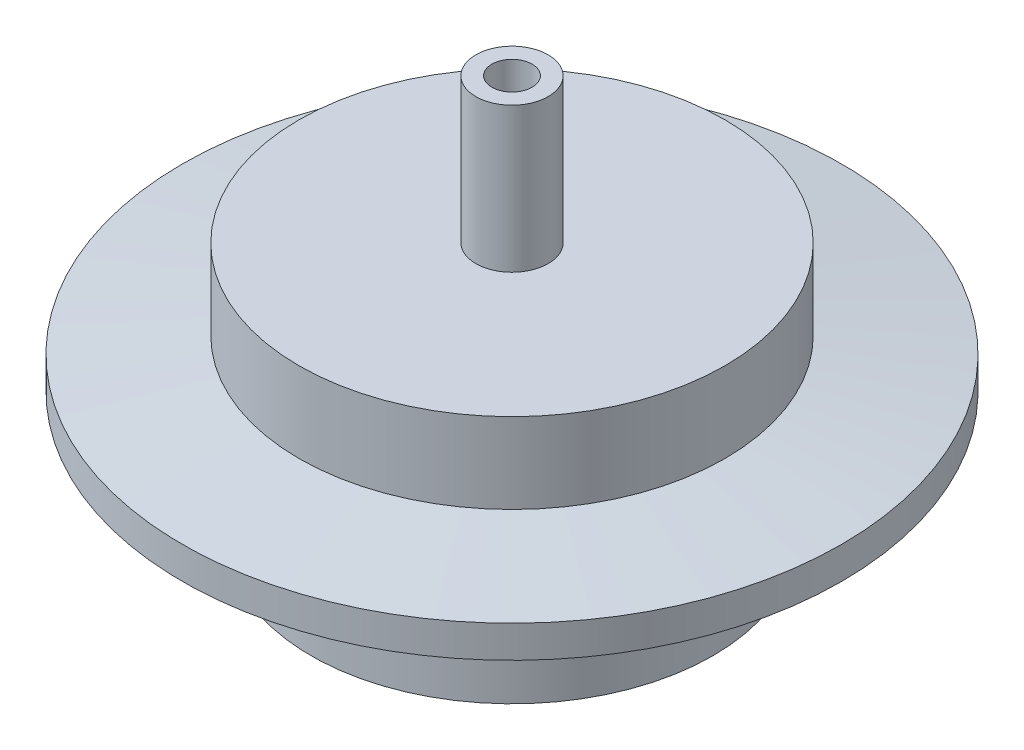
SolidWorks part; units mm, degrees
ref_plane "Front Plane" through (0, 0, 0) normal (0, 0, 1) x (1, 0, 0)
ref_plane "Top Plane" through (0, 0, 0) normal (0, 1, 0) x (1, 0, 0)
ref_plane "Right Plane" through (0, 0, 0) normal (1, 0, 0) x (0, 0, -1)
sketch "Sketch1" plane through (0, 0, 0) normal (0, 0, 1) x (1, 0, 0)
  line L0 (0, 0) -> (0, -9)
  line L1 (0, -9) -> (-11, -9)
  line L2 (-11, -9) -> (-11, -14)
  line L3 (-11, -14) -> (-18.25, -15)
  line L4 (-18.25, -15) -> (-18.25, -17)
  line L5 (-18.25, -17) -> (-10.25, -17)
  line L6 (-10.25, -17) -> (-10.25, -25)
  line L7 (-10.25, -25) -> (-8.25, -25)
  line L8 (-8.25, -25) -> (-8.25, -14)
  line L9 (-8.25, -14) -> (1, -14)
  line L10 (1, -14) -> (1, 0)
  line L11 (1, 0) -> (0, 0)
  line L12 (2.25, 0) -> (2.25, -27) construction
  dimension "D1" = 11
  dimension "D2" = 5
  dimension "D3" = 2
  dimension "D4" = 8
  dimension "D5" = 5
  dimension "D6" = 1
  dimension "D8" = 2
  dimension "D9" = 2.5
  dimension "D10" = 8
  dimension "D11" = 1
  dimension "D12" = 12.5
revolve "Revolve1" add sketch "Sketch1" angle 360 about L12
